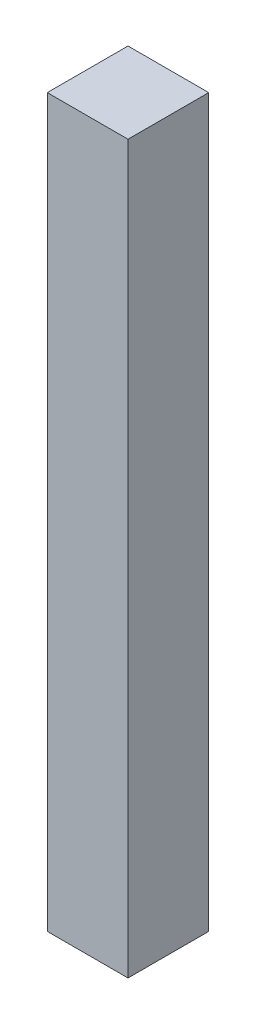
SolidWorks part; units mm, degrees
ref_plane "前视基准面" through (0, 0, 0) normal (0, 0, 1) x (1, 0, 0)
ref_plane "上视基准面" through (0, 0, 0) normal (0, 1, 0) x (1, 0, 0)
ref_plane "右视基准面" through (0, 0, 0) normal (1, 0, 0) x (0, 0, -1)
sketch "草图1" plane through (0, 0, 0) normal (0, 1, 0) x (1, 0, 0)
  line L1 (0, 0) -> (30, 0)
  line L2 (0, 0) -> (0, -30)
  line L3 (0, -30) -> (30, -30)
  line L4 (30, 0) -> (30, -30)
  dimension "D1" = 30
  dimension "D2" = 30
extrude "凸台-拉伸1" add sketch "草图1" along normal blind 270
